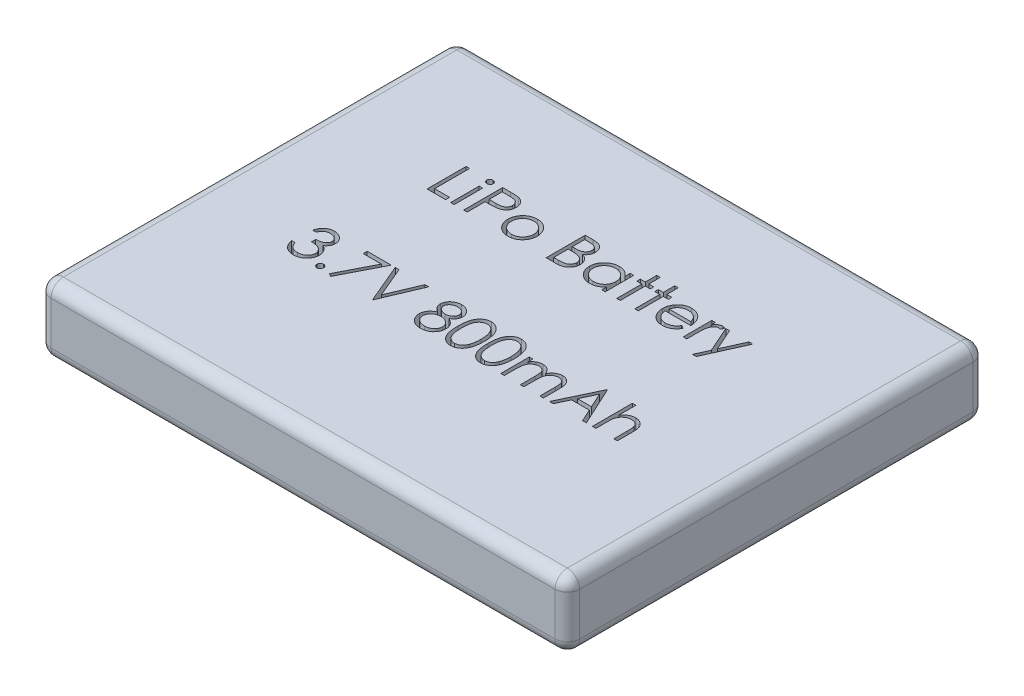
SolidWorks part; units mm, degrees
ref_plane "Front Plane" through (0, 0, 0) normal (0, 0, 1) x (1, 0, 0)
ref_plane "Top Plane" through (0, 0, 0) normal (0, 1, 0) x (1, 0, 0)
ref_plane "Right Plane" through (0, 0, 0) normal (1, 0, 0) x (0, 0, -1)
sketch "Sketch1" plane through (0, 0, 0) normal (0, 1, 0) x (1, 0, 0)
  line L1 (0, 0) -> (43, 0)
  line L2 (0, 0) -> (0, 34)
  line L3 (0, 34) -> (43, 34)
  line L4 (43, 0) -> (43, 34)
  dimension "D1" = 34
  dimension "D2" = 43
extrude "Boss-Extrude1" add sketch "Sketch1" along normal blind 5.5
fillet "Fillet1" radius 1 12 edges at (21.5, 5.5, -34) (43, 5.5, -17) (21.5, 5.5, 0) (0, 5.5, -17) (0, 2.75, -34) (0, 2.75, 0) (43, 2.75, 0) (43, 2.75, -34) (43, 0, -17) (21.5, 0, -34) (0, 0, -17) (21.5, 0, 0)
sketch "Sketch5" plane through (0, 5.5, 0) normal (0, 1, 0) x (1, 0, 0)
  line L0 (21.5, 33) -> (21.5, 1) construction
  line L1 (42, 33) -> (1, 33) construction
  line L2 (1, 1) -> (42, 1) construction
  line L3 (1, 17) -> (42, 17) construction
  line L4 (1, 33) -> (1, 1) construction
  line L5 (42, 1) -> (42, 33) construction
  line L6 (1, 12) -> (42, 12) construction
  line L7 (1, 22) -> (42, 22) construction
  text T0 "LiPo Battery"
  text T1 "3.7V 800mAh"
  dimension "D1" = 5
  dimension "D2" = 5
extrude "Cut-Extrude4" cut sketch "Sketch5" against normal blind 1
